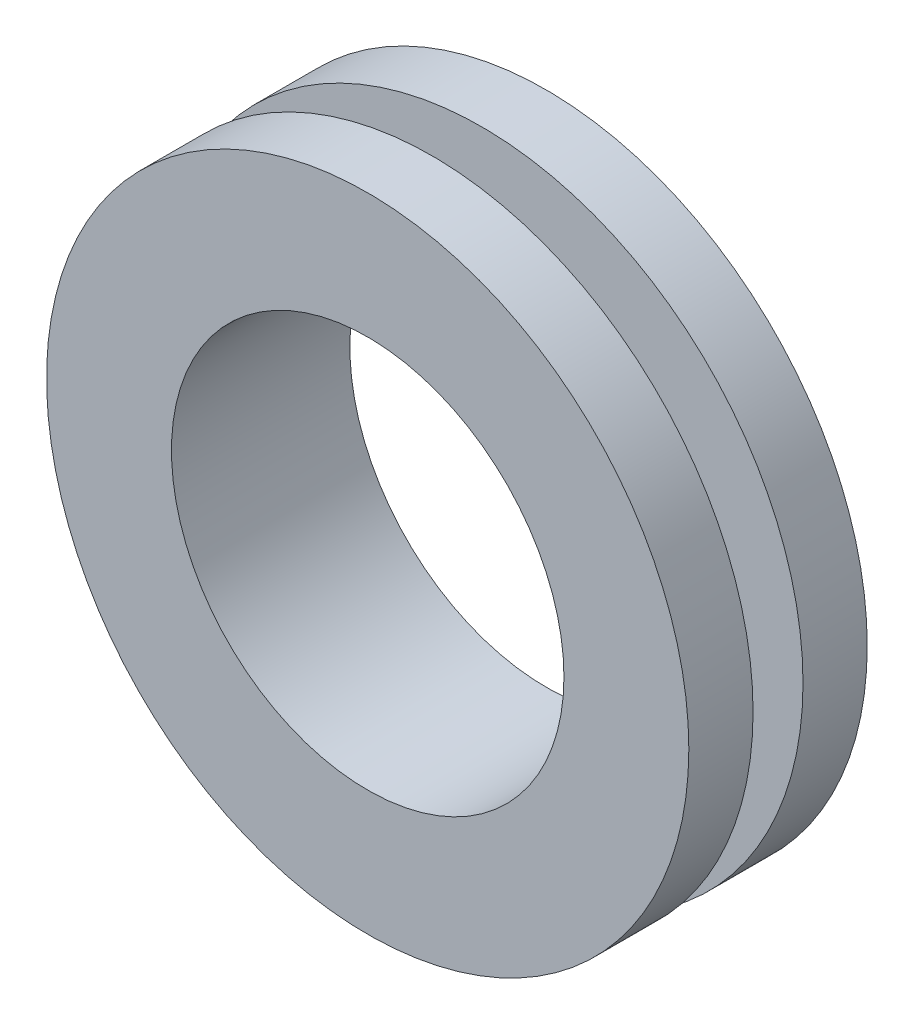
SolidWorks part; units mm, degrees
ref_plane "Front Plane" through (0, 0, 0) normal (0, 0, 1) x (1, 0, 0)
ref_plane "Top Plane" through (0, 0, 0) normal (0, 1, 0) x (1, 0, 0)
ref_plane "Right Plane" through (0, 0, 0) normal (1, 0, 0) x (0, 0, -1)
sketch "Sketch1" plane through (0, 0, 0) normal (0, 0, 1) x (1, 0, 0)
  circle A0 centre (0, 0) radius 45
  dimension "D1" = 90
extrude "Boss-Extrude1" add sketch "Sketch1" along normal blind 9
sketch "Sketch2" plane through (0, 0, 9) normal (0, 0, 1) x (1, 0, 0)
  circle A0 centre (0, 0) radius 32.5
  dimension "D1" = 65
extrude "Boss-Extrude4" add sketch "Sketch2" along normal blind 7 contours A0
sketch "Sketch4" plane through (0, 0, 16) normal (0, 0, 1) x (1, 0, 0)
  circle A0 centre (0, 0) radius 45
  dimension "D1" = 90
extrude "Boss-Extrude5" add sketch "Sketch4" along normal blind 9
sketch "Sketch5" plane through (0, 0, 25) normal (0, 0, 1) x (1, 0, 0)
  circle A0 centre (0, 0) radius 27.5
  dimension "D1" = 55
extrude "Cut-Extrude1" cut sketch "Sketch5" against normal blind 25
